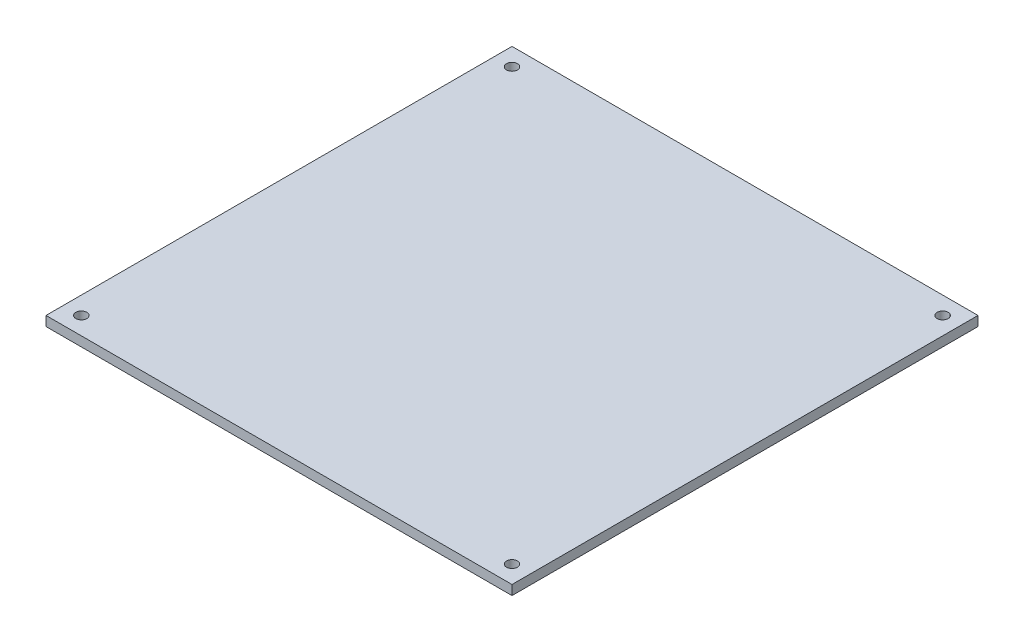
SolidWorks part; units mm, degrees
ref_plane "Front Plane" through (0, 0, 0) normal (0, 0, 1) x (1, 0, 0)
ref_plane "Top Plane" through (0, 0, 0) normal (0, 1, 0) x (1, 0, 0)
ref_plane "Right Plane" through (0, 0, 0) normal (1, 0, 0) x (0, 0, -1)
sketch "Sketch1" plane through (0, 0, 0) normal (0, 1, 0) x (1, 0, 0)
  line L1 (0, 0) -> (145, 0)
  line L2 (0, 0) -> (0, 145)
  line L3 (0, 145) -> (145, 145)
  line L4 (145, 0) -> (145, 145)
  dimension "D1" = 145
extrude "Boss-Extrude1" add sketch "Sketch1" along normal blind 3
sketch "Sketch2" plane through (0, 3, 0) normal (0, 1, 0) x (1, 0, 0)
  line L0 (0, 72.5) -> (145, 72.5) construction
  line L1 (0, 145) -> (0, 0) construction
  line L2 (145, 0) -> (145, 145) construction
  line L3 (72.5, 145) -> (72.5, 0) construction
  line L4 (145, 145) -> (0, 145) construction
  line L5 (0, 0) -> (145, 0) construction
  circle A0 centre (5.5, 5.5) radius 1.705
  circle A1 centre (139.5, 5.5) radius 1.705
  circle A2 centre (5.5, 139.5) radius 1.705
  circle A3 centre (139.5, 139.5) radius 1.705
  dimension "D3" = 3.41
  dimension "D1" = 5.5
  dimension "D2" = 5.5
extrude "Cut-Extrude1" cut sketch "Sketch2" against normal through all
